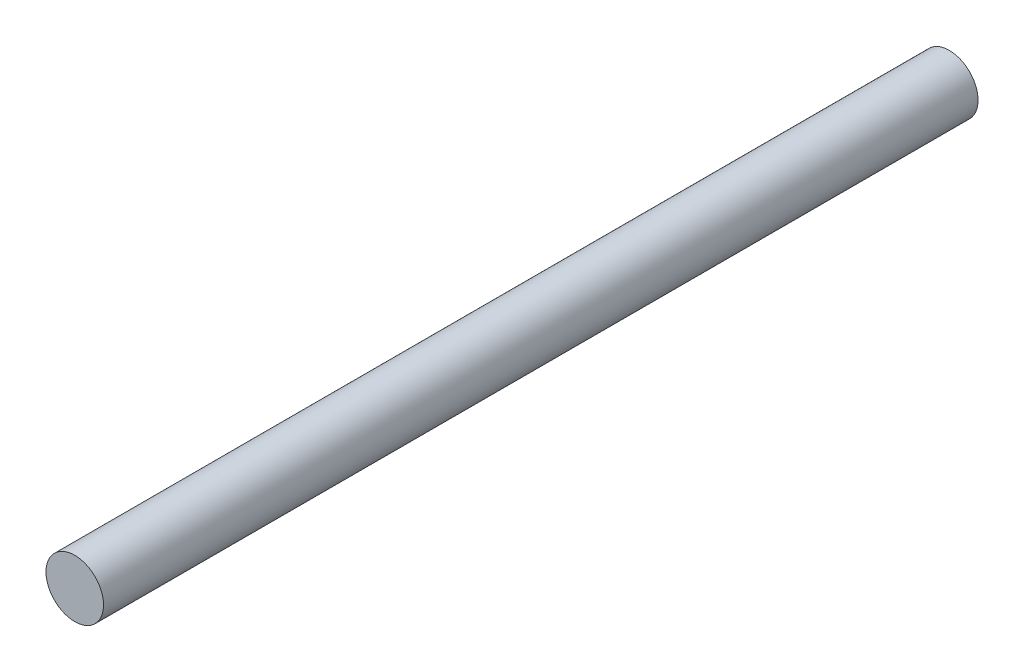
SolidWorks part; units mm, degrees
ref_plane "Front Plane" through (0, 0, 0) normal (0, 0, 1) x (1, 0, 0)
ref_plane "Top Plane" through (0, 0, 0) normal (0, 1, 0) x (1, 0, 0)
ref_plane "Right Plane" through (0, 0, 0) normal (1, 0, 0) x (0, 0, -1)
sketch "Sketch1" plane through (0, 0, 0) normal (0, 0, 1) x (1, 0, 0)
  circle A0 centre (0, 0) radius 1.5875
  dimension "D1" = 3.175
extrude "Boss-Extrude1" add sketch "Sketch1" along normal blind 48.26
